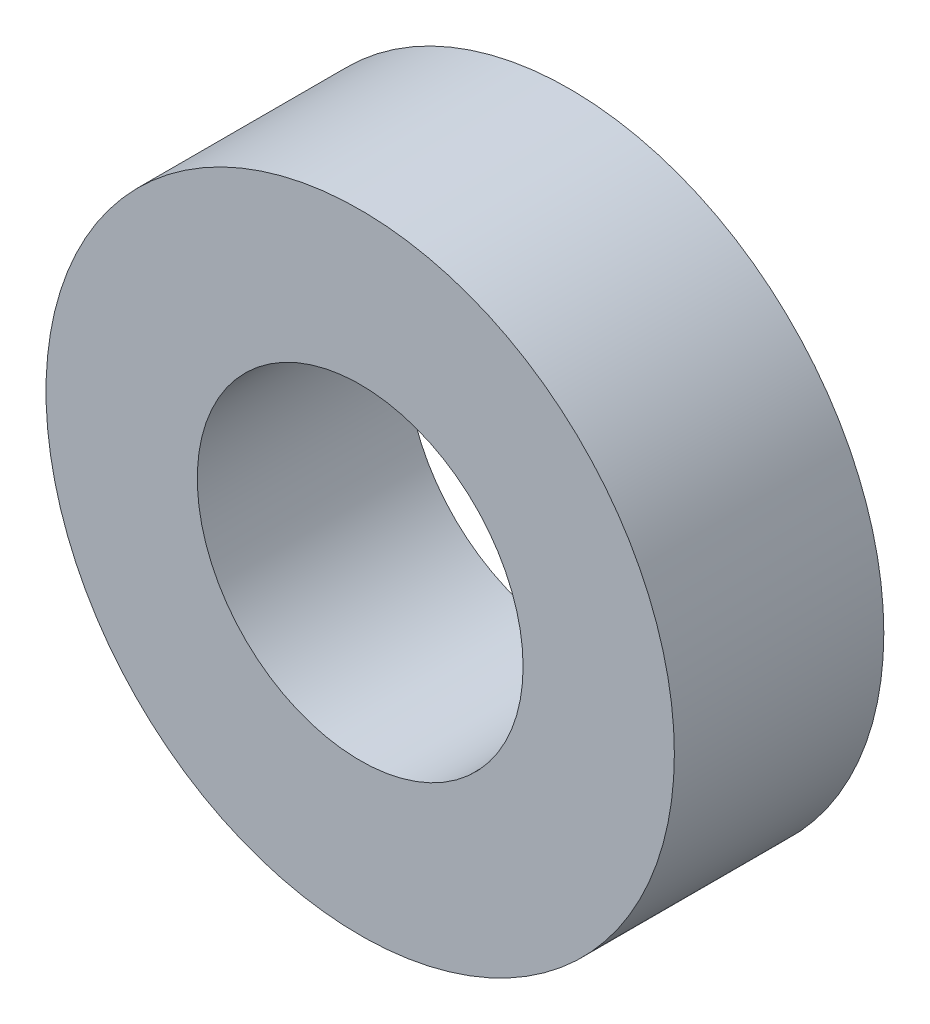
SolidWorks part; units mm, degrees
material "Простая углеродистая сталь"
ref_plane "Спереди" through (0, 0, 0) normal (0, 0, 1) x (1, 0, 0)
ref_plane "Сверху" through (0, 0, 0) normal (0, 1, 0) x (1, 0, 0)
ref_plane "Справа" through (0, 0, 0) normal (1, 0, 0) x (0, 0, -1)
sketch "Эскиз1" plane through (0, 0, 0) normal (0, 0, 1) x (1, 0, 0)
  circle A0 centre (0, 0) radius 13.5
  circle A1 centre (0, 0) radius 7
  dimension "D1" = 27
  dimension "D2" = 14
extrude "Бобышка-Вытянуть1" add sketch "Эскиз1" along normal blind 9
